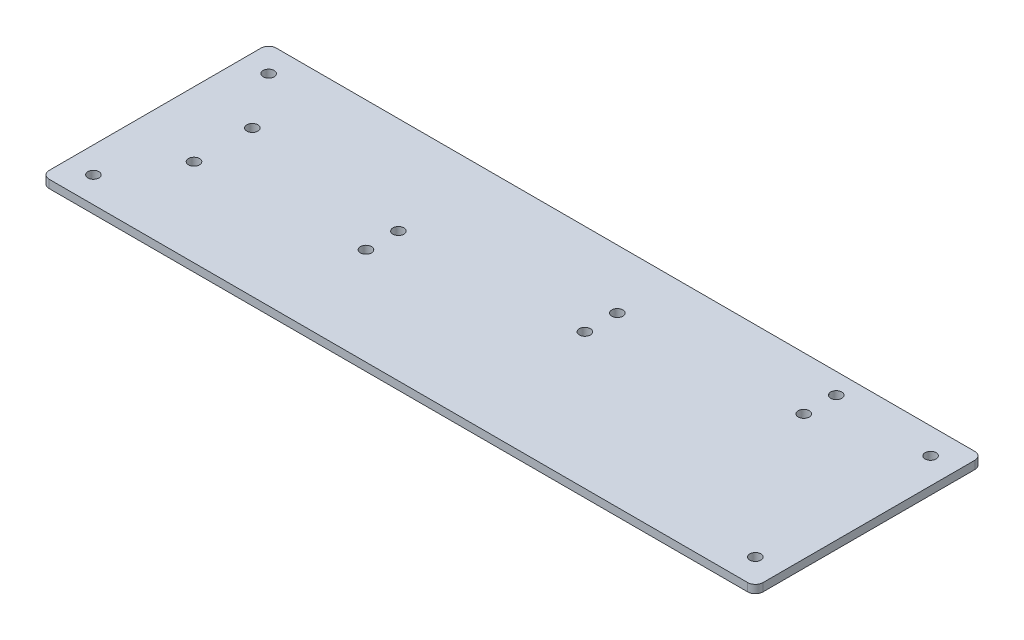
SolidWorks part; units mm, degrees
ref_plane "Front Plane" through (0, 0, 0) normal (0, 0, 1) x (1, 0, 0)
ref_plane "Top Plane" through (0, 0, 0) normal (0, 1, 0) x (1, 0, 0)
ref_plane "Right Plane" through (0, 0, 0) normal (1, 0, 0) x (0, 0, -1)
sketch "Sketch1" plane through (0, 0, 0) normal (0, 1, 0) x (1, 0, 0)
  line L1 (-139.7, 44.45) -> (139.7, 44.45)
  line L2 (-139.7, 44.45) -> (-139.7, -44.45)
  line L3 (-139.7, -44.45) -> (139.7, -44.45)
  line L4 (139.7, 44.45) -> (139.7, -44.45)
  line L5 (-139.7, 44.45) -> (139.7, -44.45) construction
  line L6 (-139.7, -44.45) -> (139.7, 44.45) construction
  point P0 (0, 0)
  dimension "D1" = 88.9
  dimension "D2" = 279.4
extrude "Boss-Extrude1" add sketch "Sketch1" along normal blind 3.175
sketch "Sketch2" plane through (0, 3.175, 0) normal (0, 1, 0) x (1, 0, 0)
  line L0 (-139.7, 44.45) -> (-139.7, -44.45) construction
  line L1 (139.7, 44.45) -> (-139.7, 44.45) construction
  line L3 (-139.7, -44.45) -> (139.7, -44.45) construction
  line L4 (139.7, 44.45) -> (139.7, -44.45) construction
  line L5 (-107.95, 0) -> (107.95, 0) construction
  line L7 (0, -44.45) -> (0, 54.1887) construction
  circle A0 centre (-114.3, 12.7) radius 2.16
  circle A1 centre (-114.3, -10.16) radius 2.16
  circle A2 centre (-50.8, 6.35) radius 2.159
  circle A3 centre (-50.8, -6.35) radius 2.159
  circle A4 centre (19.8516, 8.6675) radius 2.159
  circle A5 centre (19.8516, 21.3675) radius 2.159
  circle A6 centre (90.5032, 23.6849) radius 2.159
  circle A7 centre (90.5032, 36.3849) radius 2.159
  circle A8 centre (129.54, -34.29) radius 2.159
  circle A9 centre (-129.54, -34.29) radius 2.159
  circle A10 centre (-129.54, 34.29) radius 2.159
  circle A11 centre (129.54, 34.29) radius 2.159
  dimension "D1" = 2
  dimension "D4" = 4.32
  dimension "D5" = 4.318
  dimension "D6" = 63.5
  dimension "D10" = 4.318
  dimension "D2" = 25.4
  dimension "D3" = 31.75
  dimension "D7" = 6.35
  dimension "D11" = 10.16
  dimension "D12" = 10.16
  dimension "D8" = 2
  dimension "D9" = 3
extrude "Cut-Extrude1" cut sketch "Sketch2" against normal blind 6.35
fillet "Fillet1" radius 3 4 edges at (-139.7, 1.5875, -44.45) (-139.7, 1.5875, 44.45) (139.7, 1.5875, 44.45) (139.7, 1.5875, -44.45)
